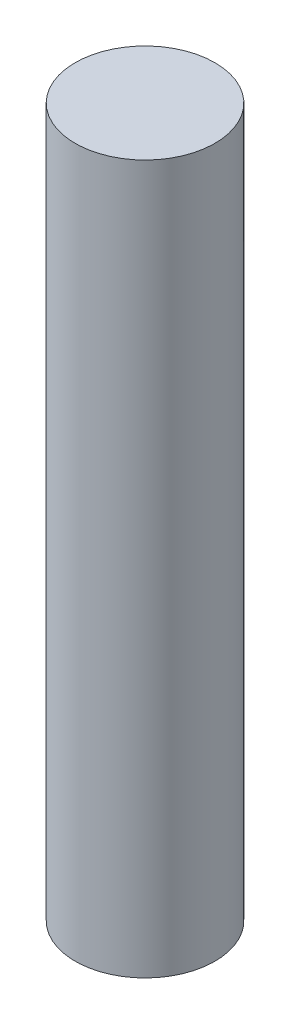
SolidWorks part; units mm, degrees
ref_plane "Front" through (0, 0, 0) normal (0, 0, 1) x (1, 0, 0)
ref_plane "Top" through (0, 0, 0) normal (0, 1, 0) x (1, 0, 0)
ref_plane "Right" through (0, 0, 0) normal (1, 0, 0) x (0, 0, -1)
sketch "Sketch1" plane through (0, 0, 0) normal (0, 1, 0) x (1, 0, 0)
  circle A0 centre (0, 0) radius 1.8796
  dimension "D1" = 3.7592
extrude "Boss-Extrude1" add sketch "Sketch1" along normal blind 19.05
